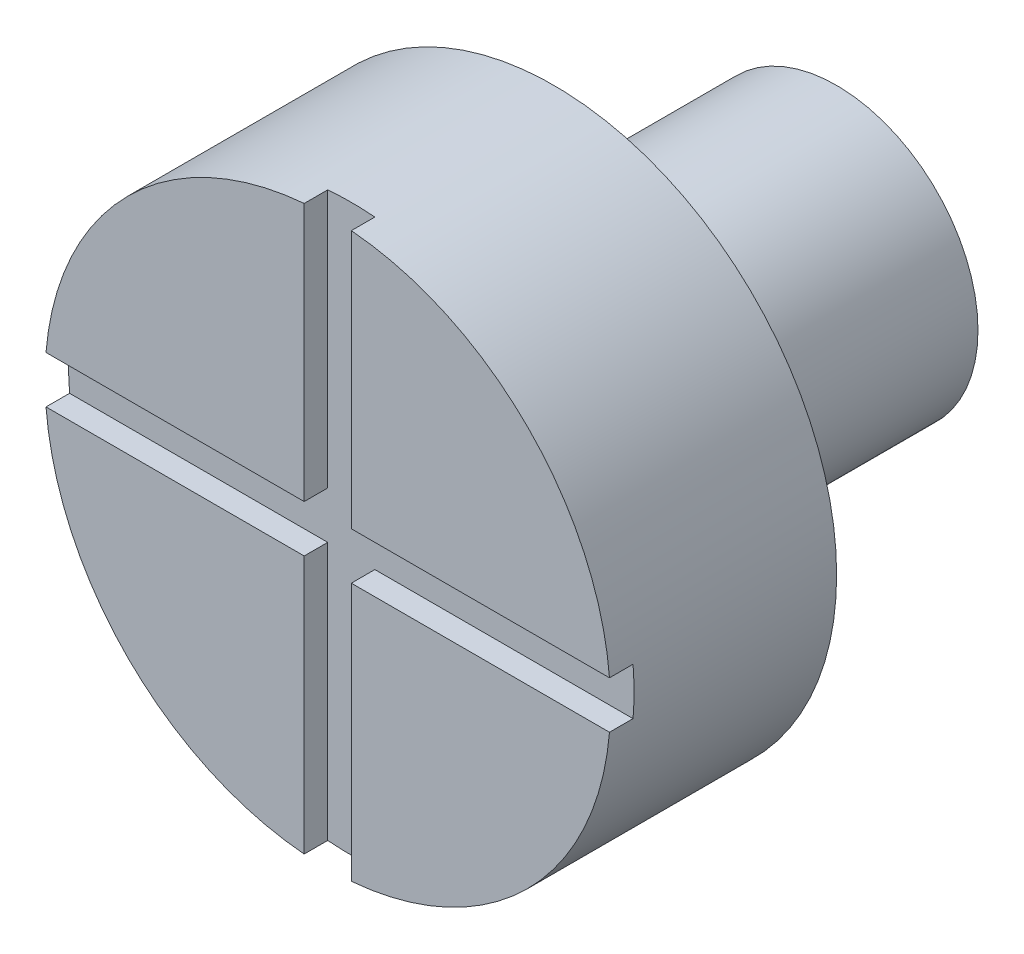
SolidWorks part; units mm, degrees
material "6061 Alloy"
ref_plane "Front Plane" through (0, 0, 0) normal (0, 0, 1) x (1, 0, 0)
ref_plane "Top Plane" through (0, 0, 0) normal (0, 1, 0) x (1, 0, 0)
ref_plane "Right Plane" through (0, 0, 0) normal (1, 0, 0) x (0, 0, -1)
sketch "Sketch1" plane through (0, 0, 0) normal (1, 0, 0) x (0, 0, -1)
  line L0 (0, 0) -> (0, 3)
  line L1 (0, 3) -> (2.4, 3)
  line L2 (2.4, 3) -> (2.4, 1.5)
  line L3 (2.4, 1.5) -> (5.4, 1.5)
  line L4 (5.4, 1.5) -> (5.4, 0)
  line L5 (0, 0) -> (5.4, 0) construction
  line L6 (0, 0) -> (5.4, 0)
  dimension "D1" = 3
  dimension "D2" = 2.4
  dimension "D3" = 1.5
  dimension "D4" = 3
revolve "Revolve1" add sketch "Sketch1" angle 360 about L5
sketch "Sketch2" plane through (0, 0, 0) normal (0, 0, 1) x (1, 0, 0)
  line L0 (0, 3) -> (0, 0.25) construction
  line L1 (-3, 0) -> (-0.25, 0) construction
  line L2 (-0.25, 3) -> (-0.25, 0.25)
  line L3 (-3, -0.25) -> (-0.25, -0.25)
  line L4 (0.25, 3) -> (0.25, 0.25)
  line L5 (-3, 0.25) -> (-0.25, 0.25)
  line L6 (2, 0.25) -> (4.0069, 0.25)
  line L7 (4.0069, 0.25) -> (4.0069, -0.3193)
  line L8 (0.25, 3) -> (0.2501, 2.0107)
  line L9 (4.0069, -0.3193) -> (3.0769, -0.25)
  line L10 (3.0769, -0.25) -> (2, -0.25)
  line L11 (-0.25, 3) -> (0, 3.4465)
  line L12 (0, 3.4465) -> (0.25, 3)
  line L13 (-3, 0.25) -> (-3.4465, 0)
  line L14 (-3.4465, 0) -> (-3, -0.25)
  line L15 (0.25, 0.25) -> (2, 0.25)
  line L16 (-3, 0.25) -> (2, 0.25) construction
  line L17 (-0.25, -2) -> (-0.25, -3.4742)
  line L18 (0, 3) -> (0, -2) construction
  line L19 (-0.25, -3.4742) -> (0.25, -3.4742)
  line L20 (-3, 0) -> (2, 0) construction
  line L21 (-0.25, -0.25) -> (-0.25, -2)
  line L22 (-0.25, 3) -> (-0.25, -2) construction
  line L23 (0.25, -0.25) -> (0.25, -2)
  line L24 (0.25, 3) -> (0.25, -2) construction
  line L25 (0.25, -0.25) -> (2, -0.25)
  line L26 (-3, -0.25) -> (2, -0.25) construction
  line L27 (0.25, -3.4742) -> (0.25, -2)
  circle A0 centre (0, 0) radius 3 construction
  dimension "D1" = 0.25
  dimension "D2" = 0.25
extrude "Cut-Extrude1" cut sketch "Sketch2" against normal blind 0.25
